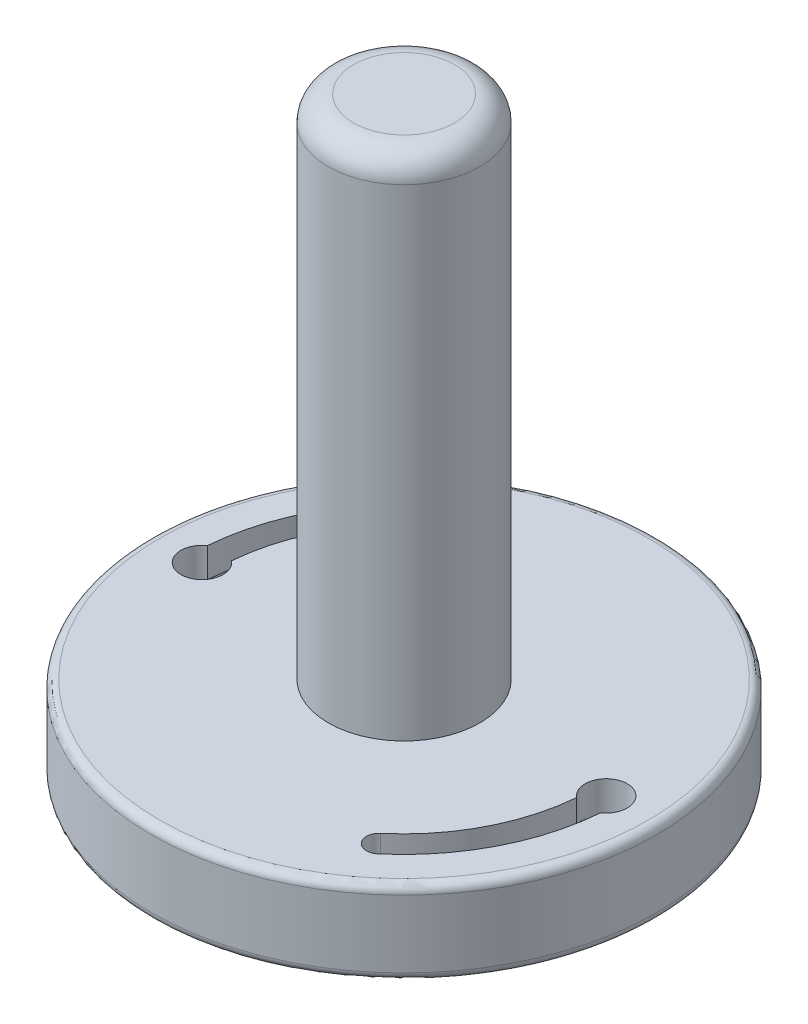
SolidWorks part; units mm, degrees
material "Nylon 101"
ref_plane "Front Plane" through (0, 0, 0) normal (0, 0, 1) x (1, 0, 0)
ref_plane "Top Plane" through (0, 0, 0) normal (0, 1, 0) x (1, 0, 0)
ref_plane "Right Plane" through (0, 0, 0) normal (1, 0, 0) x (0, 0, -1)
sketch "Sketch1" plane through (0, 0, 0) normal (0, 1, 0) x (1, 0, 0)
  circle A0 centre (0, 0) radius 38.1
extrude "Boss-Extrude1" add sketch "Sketch1" along normal blind 12.7
sketch "Sketch2" plane through (0, 12.7, 0) normal (0, 1, 0) x (1, 0, 0)
  circle A0 centre (0, 0) radius 11.43
  dimension "D1" = 22.86
extrude "Boss-Extrude2" add sketch "Sketch2" along normal blind 76.454
sketch "Sketch3" plane through (0, 0, 0) normal (0, -1, 0) x (-1, 0, 0)
  line L0 (0, 0) -> (0, -31.75)
  line L1 (0, 0) -> (-27.4963, 15.875)
  line L2 (0, 0) -> (27.4963, 15.875)
  line L3 (0, 0) -> (3.2996, 1.905)
  line L4 (0, 0) -> (-3.2996, 1.905)
  line L5 (0, 0) -> (0, -3.81)
  line L6 (-3.2996, 1.905) -> (3.2996, 1.905)
  line L7 (-3.2996, 1.905) -> (-3.2996, -31.3982)
  line L8 (3.2996, 1.905) -> (3.2996, -31.3982)
  line L9 (-3.2996, -31.3982) -> (3.2996, -31.3982)
  line L10 (0, -3.81) -> (3.2996, 1.905)
  line L11 (0, -3.81) -> (-29.105, 12.9938)
  line L12 (3.2996, 1.905) -> (-22.5059, 16.8038)
  line L13 (-29.105, 12.9938) -> (-25.8054, 18.7088)
  line L14 (0, -3.81) -> (-3.2996, 1.905)
  line L15 (0, -3.81) -> (28.9716, 12.9168)
  line L16 (-3.2996, 1.905) -> (8.9711, 8.9894)
  line L17 (28.9716, 12.9168) -> (25.672, 18.6318)
  line L18 (25.672, 18.6318) -> (23.2759, 21.5939)
  line L20 (-25.8054, 18.7088) -> (-23.2759, 21.5939)
  line L21 (-25.8054, 18.7088) -> (-25.6976, 18.6465)
  line L22 (-25.6976, 18.6465) -> (-25.8054, 18.7088)
  line L24 (-8.9711, 8.9894) -> (-12.2706, 10.8944)
  line L25 (-9.8562, 9.5005) -> (-13.1557, 11.4055)
  line L26 (-8.9711, 8.9894) -> (-5.901, 11.2458)
  line L27 (5.901, 11.2458) -> (5.8917, 11.2507)
  line L28 (12.2706, 10.8944) -> (22.3725, 16.7268)
  arc A0 (5.9327, 11.2291) -> (8.9711, 8.9894) centre (0, 0) ccw
  circle A1 centre (0, 0) radius 31.75
  arc A2 (22.3725, 16.7268) -> (23.2759, 21.5939) centre (19.9763, 19.6889) ccw
  arc A3 (-23.2759, 21.5939) -> (-22.5059, 16.8038) centre (-19.9902, 19.6651) ccw
  arc A4 (5.901, 11.2458) -> (12.2706, 10.8944) centre (9.467, 17.9799) ccw
  circle A5 centre (-9.467, 17.9799) radius 7.62
  dimension "D1" = 25.4
  dimension "D10" = 7.62
  dimension "D12" = 7.62
  dimension "D18" = 15.24
  dimension "D19" = 3.81
  dimension "D2" = 31.75
  dimension "D3" = 120
  dimension "D4" = 120
  dimension "D5" = 3.81
  dimension "D6" = 3.81
  dimension "D7" = 3.81
  dimension "D8" = 3.81
  dimension "D9" = 3.81
  dimension "D11" = 3.81
  dimension "D13" = 29.6435
  dimension "D14" = 3.81
  dimension "D15" = 3.81
  dimension "D16" = 29.7975
  dimension "D17" = 3.81
fillet "Fillet1" radius 1.27 1 edges at (0, 12.7, 38.1)
fillet "Fillet2" radius 1.27 1 edges at (0, 0, 38.1)
fillet "Fillet3" radius 3.81 1 edges at (0, 89.154, 11.43)
ref_plane "Plane1" through (0, 5.08, 0) normal (0, -1, 0) x (-1, 0, 0)
sketch "Sketch4" plane through (0, 12.7, 0) normal (0, 1, 0) x (1, 0, 0)
  line L0 (0, 0) -> (-30.48, 0) construction
  line L1 (0, 0) -> (-19.5922, 23.349) construction
  arc A0 (-32.2792, 2.616) -> (-28.4692, 2.4571) centre (-30.48, 0) ccw
  arc A1 (32.2792, -2.616) -> (28.4692, -2.4571) centre (30.48, 0) ccw
  arc A2 (-18.3677, 21.8897) -> (-28.4692, 2.4571) centre (0, 0) ccw
  arc A3 (-20.8167, 24.8083) -> (-32.2792, 2.616) centre (0, 0) ccw
  arc A4 (-18.3677, 21.8897) -> (-20.8167, 24.8083) centre (-19.5922, 23.349) ccw
  arc A5 (18.3677, -21.8897) -> (28.4692, -2.4571) centre (0, 0) ccw
  arc A6 (20.8167, -24.8083) -> (32.2792, -2.616) centre (0, 0) ccw
  arc A7 (18.3677, -21.8897) -> (20.8167, -24.8083) centre (19.5922, -23.349) ccw
  point P17 (0, 0)
  dimension "D1" = 30.48
  dimension "D2" = 3.81
  dimension "D3" = 3.175
  dimension "D4" = 1.905
  dimension "D7" = 28.575
  dimension "D5" = 50
  dimension "D6" = 2
extrude "Cut-Extrude1" cut sketch "Sketch4" against normal blind 4.445
sketch "Sketch5" plane through (0, 8.255, 0) normal (0, 1, 0) x (1, 0, 0)
  arc A0 (-21.633, 25.7812) -> (-33.655, 0) centre (0, 0) ccw
  arc A1 (-33.655, 0) -> (-27.305, 0) centre (-30.48, 0) ccw
  arc A2 (-17.5513, 20.9168) -> (-21.633, 25.7812) centre (-19.5922, 23.349) ccw
  arc A3 (-17.5513, 20.9168) -> (-27.305, 0) centre (0, 0) ccw
  arc A4 (33.655, 0) -> (27.305, 0) centre (30.48, 0) ccw
  arc A5 (17.5513, -20.9168) -> (27.305, 0) centre (0, 0) ccw
  arc A6 (21.633, -25.7812) -> (33.655, 0) centre (0, 0) ccw
  arc A7 (17.5513, -20.9168) -> (21.633, -25.7812) centre (19.5922, -23.349) ccw
  point P9 (-33.655, 0)
  point P11 (-33.655, 0)
  point P21 (0, 0)
  dimension "D1" = 6.35
  dimension "D2" = 6.35
  dimension "D3" = 2
extrude "Cut-Extrude2" cut sketch "Sketch5" against normal blind 3.175
